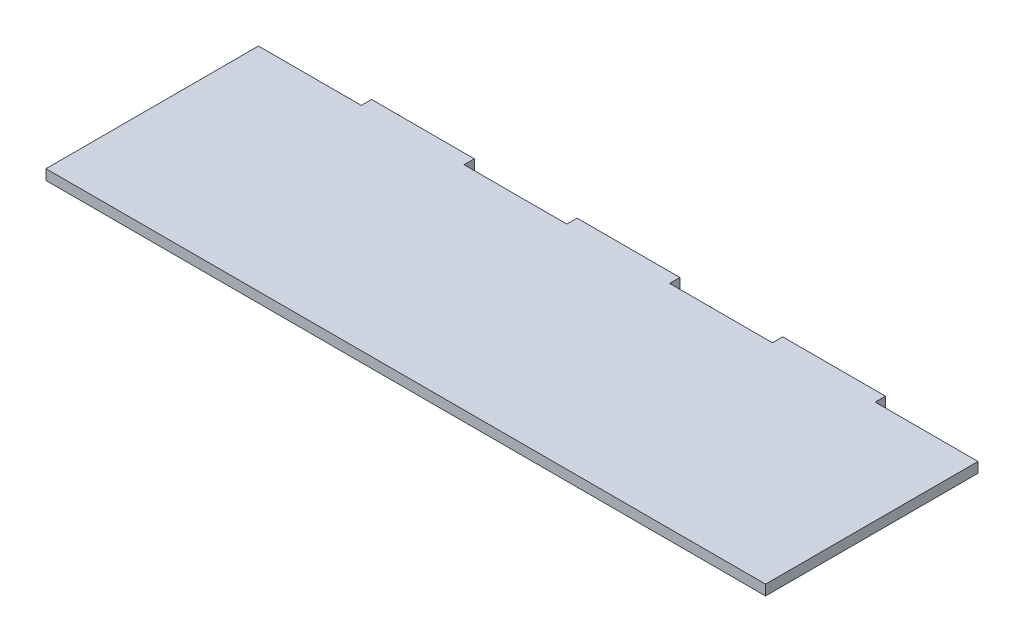
SolidWorks part; units mm, degrees
ref_plane "Front Plane" through (0, 0, 0) normal (0, 0, 1) x (1, 0, 0)
ref_plane "Top Plane" through (0, 0, 0) normal (0, 1, 0) x (1, 0, 0)
ref_plane "Right Plane" through (0, 0, 0) normal (1, 0, 0) x (0, 0, -1)
sketch "Sketch1" plane through (0, 0, 0) normal (0, 1, 0) x (1, 0, 0)
  line L1 (0, 0) -> (210, 0)
  line L2 (0, 0) -> (0, 65)
  line L3 (0, 65) -> (210, 65)
  line L4 (210, 0) -> (210, 65)
  dimension "D1" = 65
  dimension "D2" = 210
extrude "Boss-Extrude1" add sketch "Sketch1" along normal blind 3
sketch "Sketch2" plane through (0, 3, 0) normal (0, 1, 0) x (1, 0, 0)
  line L0 (210, 65) -> (0, 65) construction
  line L1 (0, 65) -> (30, 65)
  line L2 (0, 65) -> (0, 62)
  line L3 (0, 62) -> (30, 62)
  line L4 (30, 65) -> (30, 62)
  line L6 (60, 65) -> (60, 62)
  line L7 (60, 65) -> (90, 65)
  line L8 (90, 65) -> (90, 62)
  line L9 (60, 62) -> (90, 62)
  line L10 (120, 65) -> (120, 62)
  line L11 (120, 65) -> (150, 65)
  line L12 (150, 65) -> (150, 62)
  line L13 (120, 62) -> (150, 62)
  line L14 (0, 65) -> (0, 0) construction
  line L15 (180, 65) -> (180, 62)
  line L16 (180, 65) -> (210, 65)
  line L17 (210, 65) -> (210, 62)
  line L18 (180, 62) -> (210, 62)
  dimension "D1" = 30
  dimension "D3" = 3
  dimension "D5" = 30
  dimension "D4" = 4
extrude "Cut-Extrude1" cut sketch "Sketch2" against normal blind 5
